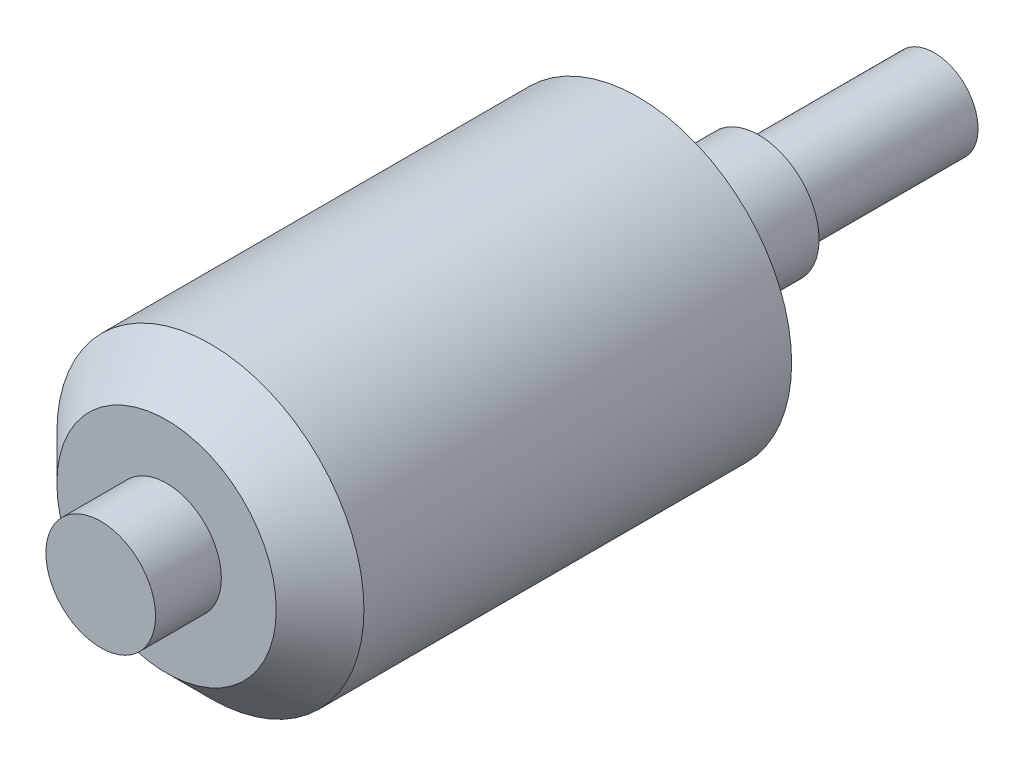
SolidWorks part; units mm, degrees
ref_plane "Plan de face" through (0, 0, 0) normal (0, 0, 1) x (1, 0, 0)
ref_plane "Plan de dessus" through (0, 0, 0) normal (0, 1, 0) x (1, 0, 0)
ref_plane "Plan de droite" through (0, 0, 0) normal (1, 0, 0) x (0, 0, -1)
sketch "Esquisse1" plane through (0, 0, 0) normal (0, 0, 1) x (1, 0, 0)
  circle A0 centre (0, 0) radius 14
  dimension "D1" = 28
extrude "Boss.-Extru.1" add sketch "Esquisse1" along normal blind 43
chamfer "Chanfrein1" distance 4 angle 45 1 edges at (14, 0, 43)
sketch "Esquisse2" plane through (0, 0, 43) normal (0, 0, 1) x (1, 0, 0)
  circle A0 centre (0, 0) radius 5
  dimension "D1" = 10
extrude "Boss.-Extru.2" add sketch "Esquisse2" along normal blind 6
sketch "Esquisse3" plane through (0, 0, 0) normal (0, 0, -1) x (-1, 0, 0)
  circle A0 centre (0, 0) radius 9.5 construction
  circle A1 centre (0, 9.5) radius 1.25
  circle A2 centre (9.5, 0) radius 1.25
  circle A3 centre (0, -9.5) radius 1.25
  circle A4 centre (-9.5, 0) radius 1.25
  point P5 (-7.3549, -1.7633)
  point P6 (0, 0)
  point P14 (0, 0)
  dimension "D1" = 19
  dimension "D2" = 2.5
  dimension "D3" = 4
extrude "Enlèv. mat.-Extru.1" cut sketch "Esquisse3" against normal blind 10
sketch "Esquisse4" plane through (0, 0, 0) normal (0, 0, -1) x (-1, 0, 0)
  circle A0 centre (0, 0) radius 2.5231
extrude "Boss.-Extru.3" add sketch "Esquisse4" along normal blind 4
sketch "Esquisse5" plane through (0, 0, -4) normal (0, 0, -1) x (-1, 0, 0)
  circle A0 centre (0, 0) radius 5.5
  dimension "D1" = 11
extrude "Boss.-Extru.4" add sketch "Esquisse5" along normal blind 7
sketch "Esquisse6" plane through (0, 0, -11) normal (0, 0, -1) x (-1, 0, 0)
  circle A0 centre (0, 0) radius 4
  dimension "D1" = 8
extrude "Boss.-Extru.5" add sketch "Esquisse6" along normal blind 16
